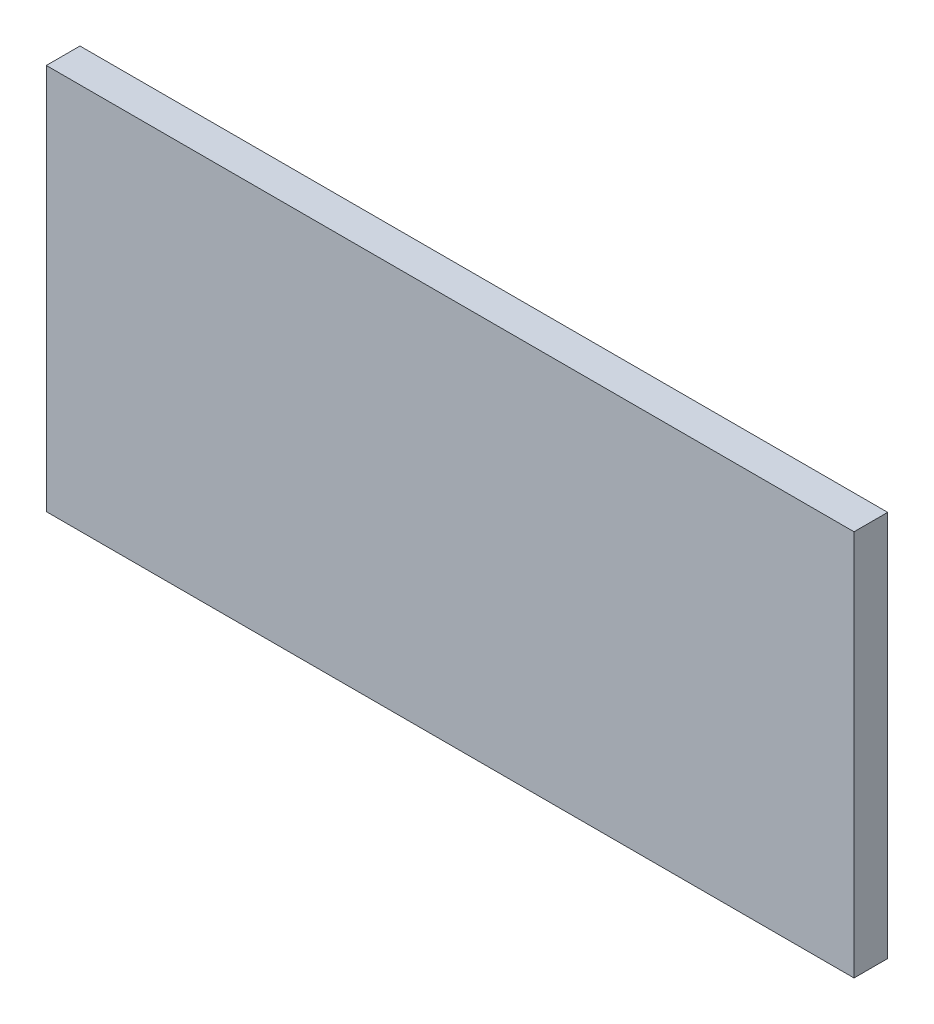
SolidWorks part; units mm, degrees
ref_plane "Alzado" through (0, 0, 0) normal (0, 0, 1) x (1, 0, 0)
ref_plane "Planta" through (0, 0, 0) normal (0, 1, 0) x (1, 0, 0)
ref_plane "Vista lateral" through (0, 0, 0) normal (1, 0, 0) x (0, 0, -1)
sketch "Croquis1" plane through (0, 0, 0) normal (0, 0, 1) x (1, 0, 0)
  line L1 (0, 0) -> (240, 0)
  line L2 (0, 0) -> (0, 114.83)
  line L3 (0, 114.83) -> (240, 114.83)
  line L4 (240, 0) -> (240, 114.83)
extrude "Saliente-Extruir1" add sketch "Croquis1" along normal blind 10
